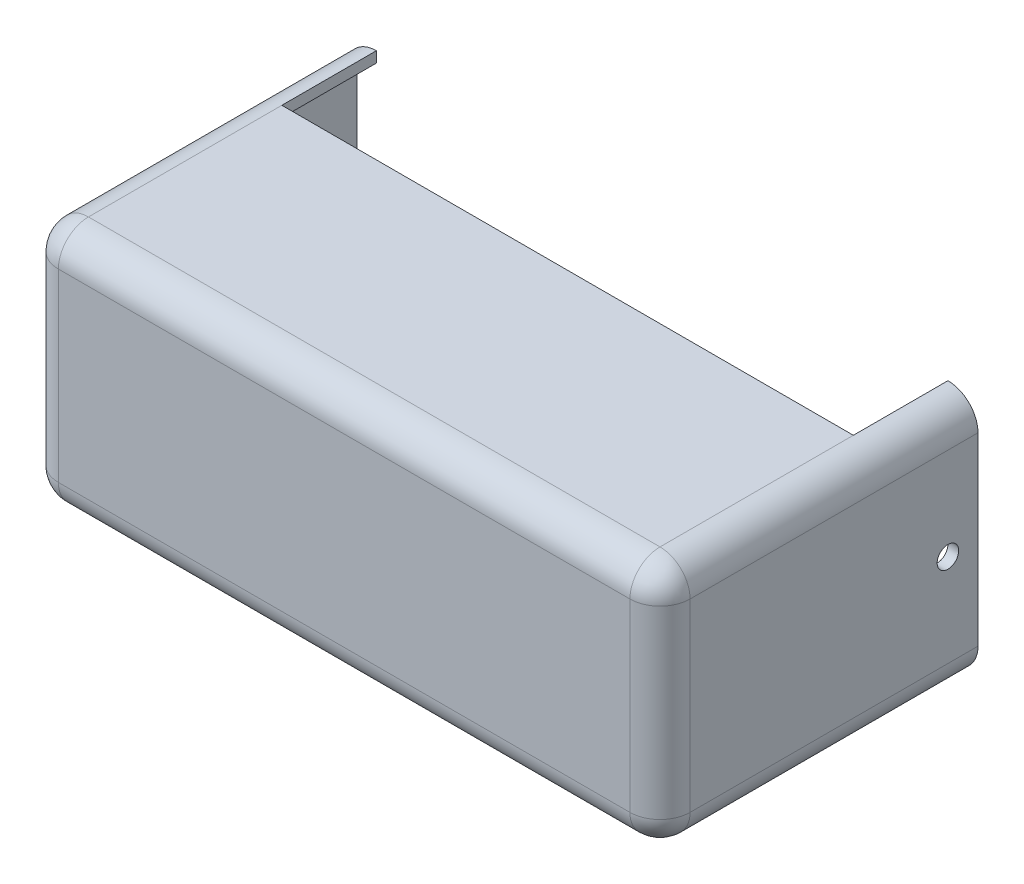
SolidWorks part; units mm, degrees
material "PE High Density"
ref_plane "Front Plane" through (0, 0, 0) normal (0, 0, 1) x (1, 0, 0)
ref_plane "Top Plane" through (0, 0, 0) normal (0, 1, 0) x (1, 0, 0)
ref_plane "Right Plane" through (0, 0, 0) normal (1, 0, 0) x (0, 0, -1)
sketch "Sketch1" plane through (0, 0, 0) normal (1, 0, 0) x (0, 0, -1)
  line L1 (0, 0) -> (132.08, 0)
  line L2 (0, 0) -> (0, 144.78)
  line L3 (0, 144.78) -> (132.08, 144.78)
  line L4 (132.08, 0) -> (132.08, 144.78)
  dimension "D1" = 132.08
  dimension "D2" = 144.78
extrude "Boss-Extrude1" add sketch "Sketch1" along normal blind 373.38
fillet "Fillet1" radius 17.78 8 edges at (373.38, 0, -66.04) (373.38, 144.78, -66.04) (0, 144.78, -66.04) (186.69, 0, 0) (186.69, 144.78, 0) (373.38, 72.39, 0) (0, 72.39, 0) (0, 0, -66.04)
shell "Shell1" thickness 6.35
sketch "Sketch2" plane through (0, 0, -132.08) normal (0, 0, -1) x (-1, 0, 0)
  line L0 (-373.38, 127) -> (-373.38, 17.78)
  line L1 (-373.38, 17.78) -> (-367.03, 17.78)
  line L2 (-367.03, 17.78) -> (-367.03, 127)
  line L3 (-367.03, 127) -> (-373.38, 127)
  line L4 (-6.35, 127) -> (0, 127)
  line L5 (0, 127) -> (0, 17.78)
  line L7 (-6.35, 17.78) -> (-6.35, 127)
  line L8 (-17.78, 138.43) -> (-17.78, 144.78)
  line L9 (-6.35, 127) -> (0, 127)
  line L10 (-17.78, 6.35) -> (-17.78, 0)
  line L11 (-6.35, 17.78) -> (0, 17.78)
  line L12 (-355.6, 6.35) -> (-355.6, 0)
  line L13 (-355.6, 144.78) -> (-355.6, 138.43)
  arc A0 (-367.03, 127) -> (-355.6, 138.43) centre (-355.6, 127) cw
  arc A1 (-373.38, 127) -> (-355.6, 144.78) centre (-355.6, 127) cw
  arc A2 (-373.38, 17.78) -> (-355.6, 0) centre (-355.6, 17.78) ccw
  arc A3 (-367.03, 17.78) -> (-355.6, 6.35) centre (-355.6, 17.78) ccw
  arc A4 (-6.35, 127) -> (-17.78, 138.43) centre (-17.78, 127) ccw
  arc A5 (-17.78, 144.78) -> (0, 127) centre (-17.78, 127) cw
  arc A6 (-17.78, 0) -> (0, 17.78) centre (-17.78, 17.78) ccw
  arc A7 (-6.35, 17.78) -> (-17.78, 6.35) centre (-17.78, 17.78) cw
  arc M2 (-355.6, 6.35) -> (-367.03, 17.78) centre (-355.6, 17.78) cw
  line M3 (-367.03, 17.78) -> (-367.03, 127)
  arc M4 (-367.03, 127) -> (-355.6, 138.43) centre (-355.6, 127) cw
  arc M6 (-17.78, 138.43) -> (-6.35, 127) centre (-17.78, 127) cw
  line M7 (-6.35, 127) -> (-6.35, 17.78)
  arc M8 (-6.35, 17.78) -> (-17.78, 6.35) centre (-17.78, 17.78) cw
  arc M10 (-17.78, 0) -> (0, 17.78) centre (-17.78, 17.78) ccw
  line M11 (0, 17.78) -> (0, 127)
  arc M12 (0, 127) -> (-17.78, 144.78) centre (-17.78, 127) ccw
  arc M14 (-355.6, 144.78) -> (-373.38, 127) centre (-355.6, 127) ccw
  line M15 (-373.38, 127) -> (-373.38, 17.78)
  arc M16 (-373.38, 17.78) -> (-355.6, 0) centre (-355.6, 17.78) ccw
extrude "Boss-Extrude2" add sketch "Sketch2" along normal blind 55.88 contours L13 L3 M14 M4 | L3 L1 M3 M15 | L12 L1 M2 M16 | L8 L4 M6 M12 | L11 L4 M7 M11 | L11 L10 M8 M10
sketch "Sketch3" plane through (373.38, 0, 0) normal (1, 0, 0) x (0, 0, -1)
  line L0 (187.96, 72.39) -> (0, 72.39) construction
  line L1 (187.96, 127) -> (187.96, 17.78) construction
  circle A0 centre (170.18, 72.39) radius 6.35
  dimension "D2" = 12.7
  dimension "D1" = 17.78
extrude "Cut-Extrude1" cut sketch "Sketch3" against normal blind 383.54
